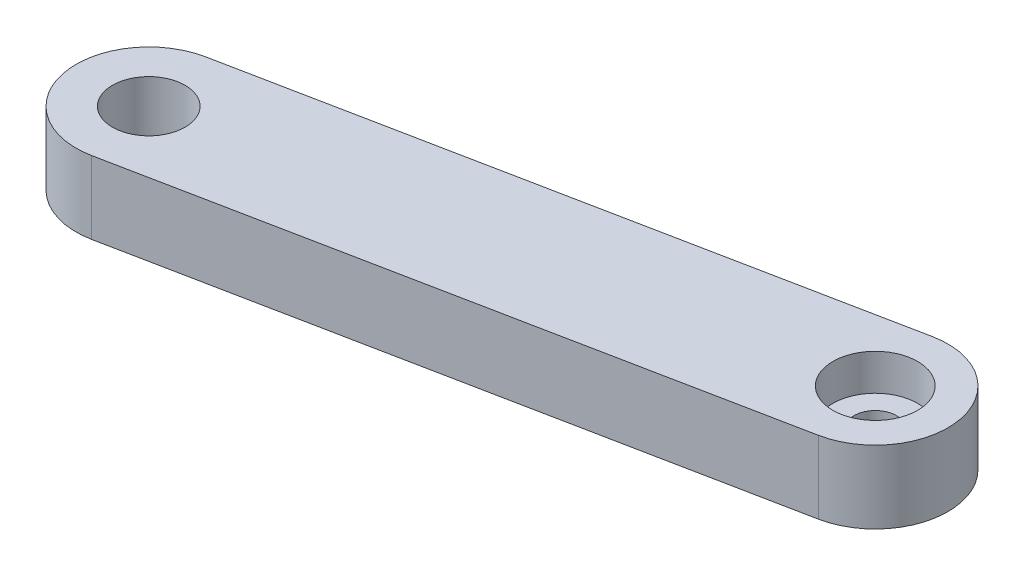
SolidWorks part; units mm, degrees
material "3D printed plastic"
ref_plane "Front Plane" through (0, 0, 0) normal (0, 0, 1) x (1, 0, 0)
ref_plane "Top Plane" through (0, 0, 0) normal (0, 1, 0) x (1, 0, 0)
ref_plane "Right Plane" through (0, 0, 0) normal (1, 0, 0) x (0, 0, -1)
sketch "Sketch1" plane through (0, 0, 0) normal (0, 1, 0) x (1, 0, 0)
  line L0 (0, 0) -> (-50, -10) construction
  line L1 (1.1767, -5.8835) -> (-48.8233, -15.8835)
  line L2 (-1.1767, 5.8835) -> (-51.1767, -4.1165)
  circle A0 centre (0, 0) radius 1.75
  circle A1 centre (-50, -10) radius 3
  arc A2 (1.1767, -5.8835) -> (-1.1767, 5.8835) centre (0, 0) ccw
  arc A3 (-51.1767, -4.1165) -> (-48.8233, -15.8835) centre (-50, -10) ccw
  point P5 (-25, -5)
  dimension "D1" = 50
  dimension "D2" = 10
  dimension "D3" = 3.5
  dimension "D5" = 6
  dimension "D4" = 12
extrude "Boss-Extrude1" add sketch "Sketch1" along normal blind 6
sketch "Sketch2" plane through (0, 6, 0) normal (0, 1, 0) x (1, 0, 0)
  circle A0 centre (0, 0) radius 3.5
  dimension "D1" = 7
extrude "Cut-Extrude1" cut sketch "Sketch2" against normal blind 3
